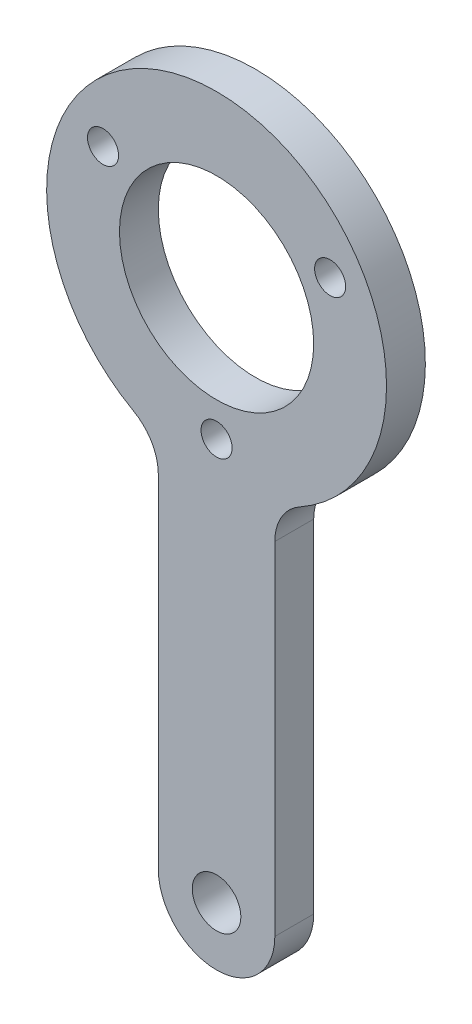
SolidWorks part; units mm, degrees
material "Thornel Mat VMA"
ref_plane "前视基准面" through (0, 0, 0) normal (0, 0, 1) x (1, 0, 0)
ref_plane "上视基准面" through (0, 0, 0) normal (0, 1, 0) x (1, 0, 0)
ref_plane "右视基准面" through (0, 0, 0) normal (1, 0, 0) x (0, 0, -1)
sketch "草图1" plane through (0, 0, 0) normal (0, 0, 1) x (1, 0, 0)
  line L0 (0, 0) -> (0, -45) construction
  line L1 (6, -7.3655) -> (6, -45)
  line L2 (-6, -7.3655) -> (-6, -45)
  arc A0 (6, -7.3655) -> (-6, -7.3655) centre (0, 0) ccw
  arc A2 (-6, -45) -> (6, -45) centre (0, -45) ccw
  point P3 (0, -25)
  dimension "D1" = 45
  dimension "D2" = 19
  dimension "D3" = 6
extrude "凸台-拉伸1" add sketch "草图1" along normal blind 4
sketch "草图3" plane through (0, 0, 4) normal (0, 0, 1) x (1, 0, 0)
  circle A0 centre (0, -45) radius 2.5
  dimension "D1" = 5
extrude "切除-拉伸1" cut sketch "草图3" against normal blind 24
sketch "草图4" plane through (0, 0, 4) normal (0, 0, 1) x (1, 0, 0)
  circle A0 centre (0, 0) radius 6.25 construction
  circle A1 centre (0, 6.25) radius 1.525
  circle A2 centre (0, -6.25) radius 1.525
  dimension "D1" = 12.5
  dimension "D2" = 3.05
extrude "切除-拉伸2" cut sketch "草图4" against normal blind 5
sketch "草图5" plane through (0, 0, 4) normal (0, 0, 1) x (1, 0, 0)
  circle A0 centre (0, 0) radius 2.5
  dimension "D1" = 5
extrude "切除-拉伸3" cut sketch "草图5" against normal blind 5
fillet "圆角1" radius 5 2 edges at (6, -7.3655, 2) (-6, -7.3655, 2)
sketch "草图6" plane through (0, 0, 4) normal (0, 0, 1) x (1, 0, 0)
  circle A0 centre (0, 0) radius 13.5 construction
  circle A1 centre (0, -13.5) radius 1.6
  circle A2 centre (-11.6913, 6.75) radius 1.6
  circle A3 centre (11.6913, 6.75) radius 1.6
  circle A4 centre (0, 0) radius 17.5
  circle A5 centre (0, 0) radius 10
  point P11 (0, 0)
  dimension "D2" = 27
  dimension "D3" = 3.2
  dimension "D4" = 35
  dimension "D5" = 20
  dimension "D1" = 3
extrude "切除-拉伸4" cut sketch "草图6" against normal blind 10 contours A1 | A5
sketch "草图7" plane through (0, 0, 4) normal (0, 0, 1) x (1, 0, 0)
  circle A1 centre (0, 0) radius 10
  circle A2 centre (0, 0) radius 10
  circle A3 centre (0, 0) radius 17.5
  circle A4 centre (0, 0) radius 17.5
  circle A5 centre (11.6913, 6.75) radius 1.6
  circle A6 centre (11.6913, 6.75) radius 1.6
  circle A7 centre (-11.6913, 6.75) radius 1.6
  circle A8 centre (-11.6913, 6.75) radius 1.6
  circle A9 centre (0, -13.5) radius 1.6
  circle A10 centre (0, -13.5) radius 1.6
  dimension "D1" = 0
  dimension "D2" = 0
  dimension "D3" = 0
  dimension "D4" = 0
  dimension "D5" = 0
extrude "凸台-拉伸2" add sketch "草图7" against normal blind 4
fillet "圆角2" radius 5 2 edges at (-6, -16.4393, 2) (6, -16.4393, 2)
sketch "草图8" plane through (0, 0, 4) normal (0, 0, 1) x (1, 0, 0)
  line L1 (-6, -54.8489) -> (-6, -40)
  line L2 (-6, -19.6278) -> (-6, -45) construction
  line L3 (-6, -40) -> (6, -40)
  line L4 (6, -45) -> (6, -19.6278) construction
  line L5 (6, -40) -> (6, -54.8489)
  circle A0 centre (0, -54.8489) radius 6
  arc A1 (-6, -45) -> (6, -45) centre (0, -45) ccw construction
  circle A2 centre (0, -54.8489) radius 2.5
  circle A3 centre (0, -45) radius 2.5 construction
  line M3 (6, -45) -> (6, -19.6278)
  line M7 (-6, -19.6278) -> (-6, -45)
  arc M8 (-6, -45) -> (6, -45) centre (0, -45) ccw
  circle M9 centre (0, -45) radius 2.5
  dimension "D1" = 40
  dimension "D2" = 54.8489
extrude "凸台-拉伸3" add sketch "草图8" against normal blind 4 contours A0 L5 M8 | A0 L1 M8 | A0 L3 M8 M3 M7 M9 | A0 A2 M8
sketch "草图9" plane through (0, 0, 4) normal (0, 0, 1) x (1, 0, 0)
  circle A0 centre (0, -45) radius 2.5 construction
  circle A1 centre (0, -45) radius 2.5
extrude "凸台-拉伸4" add sketch "草图9" against normal blind 4
